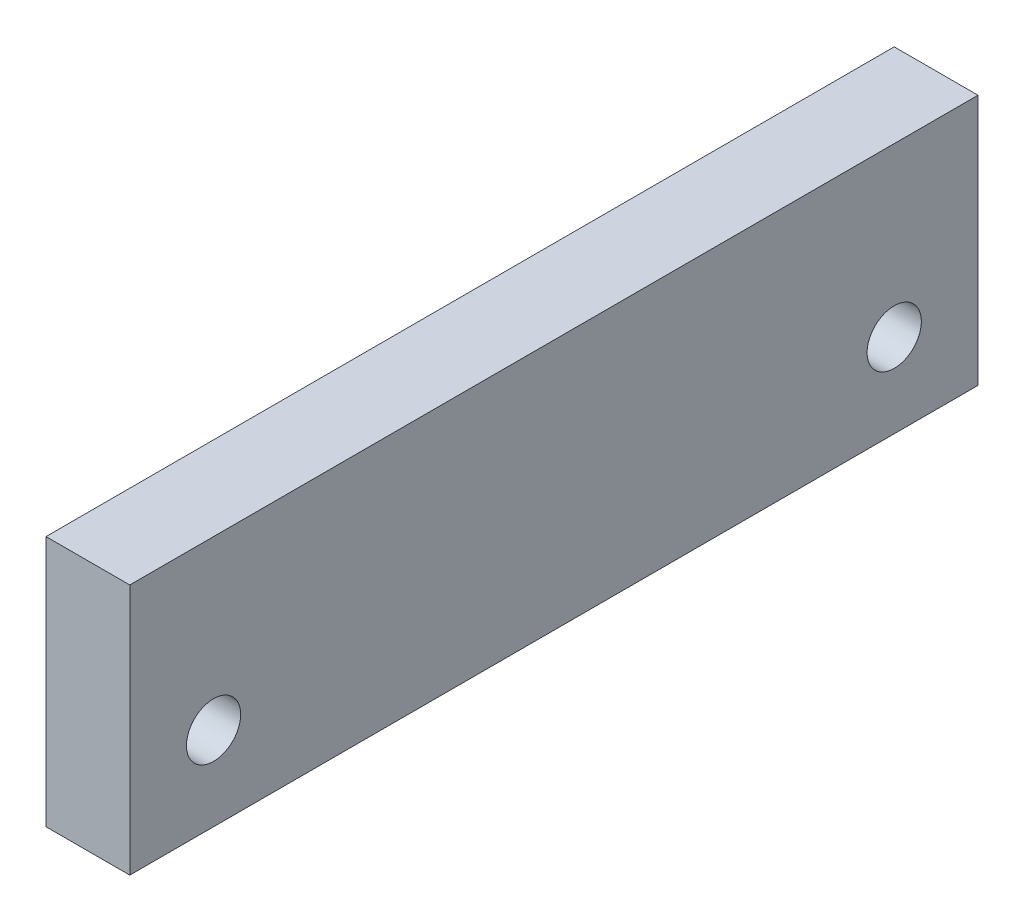
SolidWorks part; units mm, degrees
ref_plane "Front" through (0, 0, 0) normal (0, 0, 1) x (1, 0, 0)
ref_plane "Top" through (0, 0, 0) normal (0, 1, 0) x (1, 0, 0)
ref_plane "Right" through (0, 0, 0) normal (1, 0, 0) x (0, 0, -1)
sketch "Sketch1" plane through (0, 0, 0) normal (1, 0, 0) x (0, 0, -1)
  line L0 (-103.1875, 0) -> (103.1875, 0) construction
  line L1 (-128.5875, 50.8) -> (128.5875, 50.8)
  line L2 (-128.5875, 50.8) -> (-128.5875, -25.4)
  line L3 (-128.5875, -25.4) -> (128.5875, -25.4)
  line L4 (128.5875, 50.8) -> (128.5875, -25.4)
  line L5 (0, -25.4) -> (0, 50.8) construction
  circle A0 centre (-103.1875, 0) radius 8.2279
  circle A1 centre (103.1875, 0) radius 8.2279
  dimension "D1" = 25.4
  dimension "D2" = 76.2
  dimension "D3" = 206.375
  dimension "D4" = 25.4
extrude "Extrude1" add sketch "Sketch1" along normal mid plane 25.4
